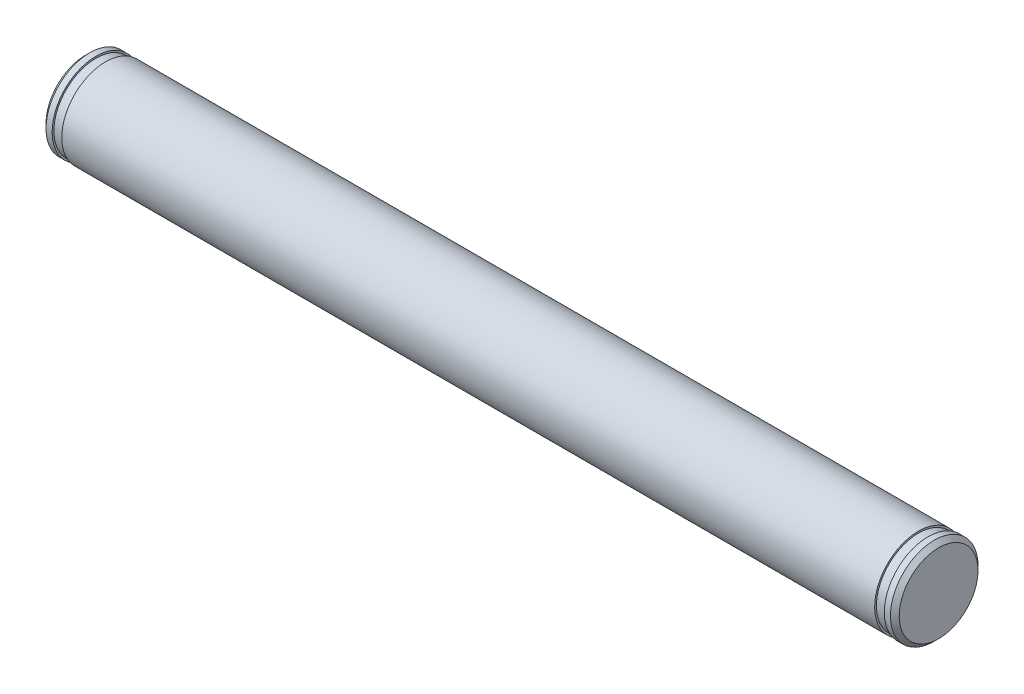
SolidWorks part; units mm, degrees
ref_plane "前视基准面" through (0, 0, 0) normal (0, 0, 1) x (1, 0, 0)
ref_plane "上视基准面" through (0, 0, 0) normal (0, 1, 0) x (1, 0, 0)
ref_plane "右视基准面" through (0, 0, 0) normal (1, 0, 0) x (0, 0, -1)
other "Configuration Table"
sketch "草图1" plane through (0, 0, 0) normal (0, 0, 1) x (1, 0, 0)
  line L0 (-48.7, 0) -> (48.7, 0) construction
  line L1 (48.7, 0) -> (48.7, 5)
  line L2 (48.7, 5) -> (47.5, 5)
  line L3 (47.5, 5) -> (47.5, 4.8)
  line L4 (47.5, 4.8) -> (46.4, 4.8)
  line L5 (46.4, 4.8) -> (46.4, 5)
  line L6 (46.4, 5) -> (-46.4, 5)
  line L7 (0, 5) -> (0, 0) construction
  line L8 (46.5, 4.8) -> (46.5, 0) construction
  line L9 (-48.7, 0) -> (-48.7, 5)
  line L10 (-46.5, 4.8) -> (-46.5, 0) construction
  line L11 (-46.4, 4.8) -> (-46.4, 5)
  line L12 (-47.5, 4.8) -> (-46.4, 4.8)
  line L13 (-47.5, 5) -> (-47.5, 4.8)
  line L14 (-48.7, 5) -> (-47.5, 5)
  line L15 (48.7, 0) -> (-48.7, 0)
  dimension "D1" = 1.1
  dimension "D2" = 1
  dimension "D3" = 10
  dimension "D4" = 9.6
  dimension "D5" = 1.2
  dimension "D6" = 93
revolve "旋转1" add sketch "草图1" angle 360 about L15
chamfer "倒角1" distance 0.5 angle 45 2 edges at (48.7, 5, 0) (-48.7, 5, 0)
ref_plane "基准面1" through (-46.5, 0, 0) normal (-1, 0, 0) x (0, 0, 1)
